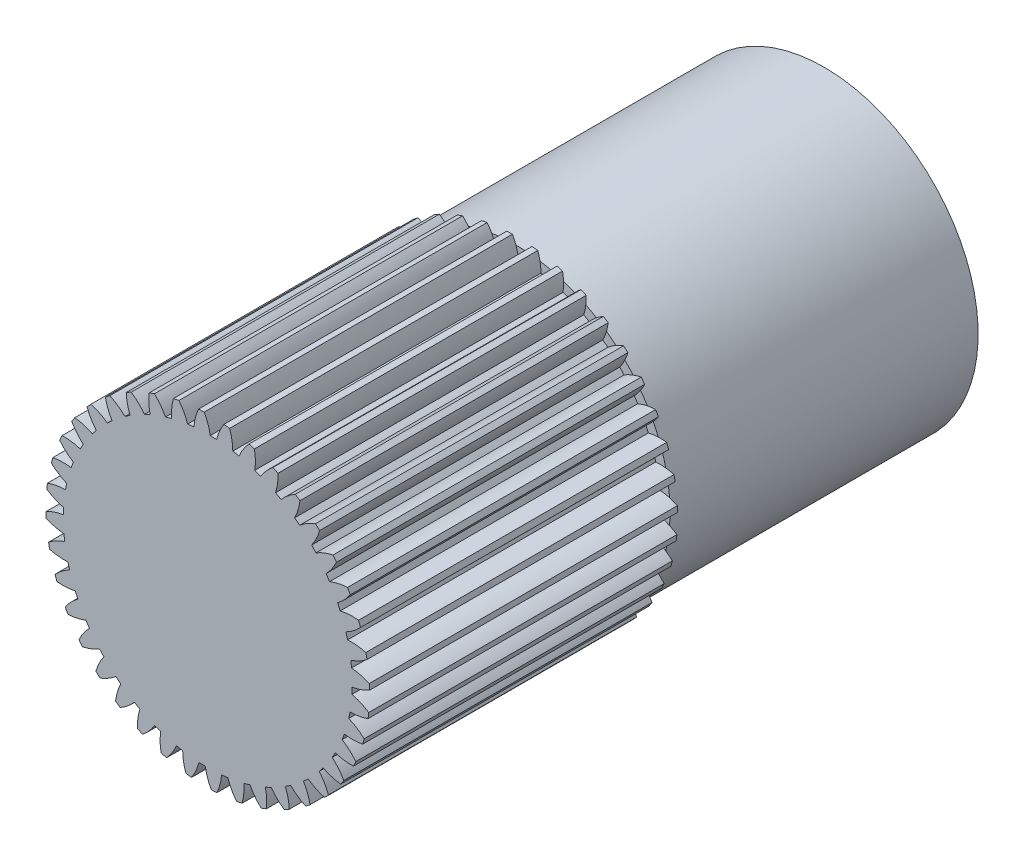
SolidWorks part; units mm, degrees
ref_plane "前视基准面" through (0, 0, 0) normal (0, 0, 1) x (1, 0, 0)
ref_plane "上视基准面" through (0, 0, 0) normal (0, 1, 0) x (1, 0, 0)
ref_plane "右视基准面" through (0, 0, 0) normal (1, 0, 0) x (0, 0, -1)
other "Configuration Table"
sketch "草图1" plane through (0, 0, 0) normal (0, 0, 1) x (1, 0, 0)
  circle A0 centre (0, 0) radius 46.875
  dimension "D1" = 93.75
extrude "凸台-拉伸1" add sketch "草图1" along normal blind 100
sketch "草图2" plane through (0, 0, 100) normal (0, 0, 1) x (1, 0, 0)
  line L0 (0, 0) -> (0, -58.9554) construction
  line L1 (0, 0) -> (24.4906, -67.2873) construction
  line L2 (0, 0) -> (2.42, -61.5926) construction
  line L3 (0, -50) -> (16.0697, -44.1511) construction
  circle A1 centre (0, 0) radius 46.875
  arc A2 (-0.8141, -46.8679) -> (4.4888, -46.6596) centre (0, 0) ccw
  circle A3 centre (0, 0) radius 50 construction
  arc A4 (-0.8141, -46.8679) -> (1.1383, -52.4877) centre (16.0697, -44.1511) ccw
  arc A5 (4.4888, -46.6596) -> (2.9833, -52.4152) centre (-12.5561, -45.2758) cw
  arc A6 (1.1383, -52.4877) -> (2.9833, -52.4152) centre (0, 0) ccw
  dimension "D3" = 100
  dimension "D4" = 20
  dimension "D5" = 2.25
  dimension "D1" = 0
extrude "凸台-拉伸2" add sketch "草图2" against normal up to surface (100 mm away) up to face at (46.875, 0, 0)
pattern_circular "阵列(圆周)1" count 40 over 360 about axis through (0, 0, 0) along (0, 0, 1) of "凸台-拉伸2"
sketch "草图3" plane through (0, 0, 0) normal (0, 0, -1) x (-1, 0, 0)
  circle A0 centre (0, 0) radius 50
  dimension "D1" = 100
extrude "凸台-拉伸3" add sketch "草图3" along normal blind 100
